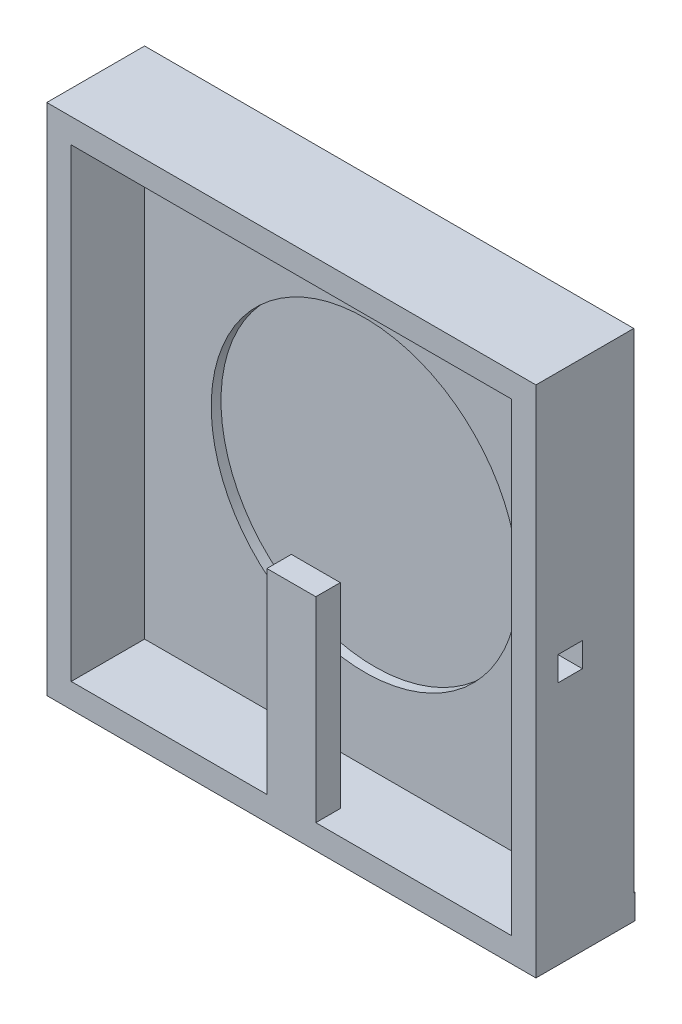
SolidWorks part; units mm, degrees
ref_plane "Front Plane" through (0, 0, 0) normal (0, 0, 1) x (1, 0, 0)
ref_plane "Top Plane" through (0, 0, 0) normal (0, 1, 0) x (1, 0, 0)
ref_plane "Right Plane" through (0, 0, 0) normal (1, 0, 0) x (0, 0, -1)
sketch "Sketch1" plane through (0, 0, 0) normal (0, 1, 0) x (1, 0, 0)
  line L1 (-750, 500) -> (750, 500)
  line L2 (-750, 500) -> (-750, -500)
  line L3 (-750, -500) -> (750, -500)
  line L4 (750, 500) -> (750, -500)
  line L5 (-750, 500) -> (750, -500) construction
  line L6 (-750, -500) -> (750, 500) construction
  point P0 (0, 0)
  dimension "D1" = 1500
  dimension "D2" = 1000
extrude "Boss-Extrude1" add sketch "Sketch1" along normal blind 50
sketch "Sketch2" plane through (0, 0, 0) normal (0, 0, 1) x (1, 0, 0)
  line L0 (-750, 50) -> (750, 50) construction
  line L1 (-500, 1050) -> (500, 1050)
  line L2 (-500, 1050) -> (-500, 50)
  line L3 (-500, 50) -> (500, 50)
  line L4 (500, 1050) -> (500, 50)
  point P6 (0, 50)
  dimension "D1" = 1000
  dimension "D2" = 1000
extrude "Boss-Extrude2" add sketch "Sketch2" against normal blind 200
sketch "Sketch3" plane through (0, 0, 0) normal (0, 0, 1) x (1, 0, 0)
  line L0 (-500, 50) -> (500, 50) construction
  line L5 (-450, 1000) -> (450, 1000)
  line L6 (-450, 1000) -> (-450, 50)
  line L7 (-450, 50) -> (450, 50)
  line L8 (450, 1000) -> (450, 50)
  line L9 (500, 50) -> (500, 1050) construction
  dimension "D1" = 900
  dimension "D2" = 50
  dimension "D3" = 950
extrude "Cut-Extrude1" cut sketch "Sketch3" against normal blind 150
sketch "Sketch4" plane through (0, 50, 0) normal (0, 1, 0) x (1, 0, 0)
  line L1 (-50, 50) -> (50, 50)
  line L2 (-50, 50) -> (-50, 0)
  line L3 (-50, 0) -> (50, 0)
  line L4 (50, 50) -> (50, 0)
  line L5 (450, 150) -> (450, 0) construction
  line L7 (-450, 150) -> (450, 150) construction
  dimension "D1" = 50
  dimension "D2" = 400
  dimension "D3" = 100
  dimension "D4" = 100
extrude "Boss-Extrude3" add sketch "Sketch4" along normal blind 400
sketch "Sketch5" plane through (500, 0, 0) normal (1, 0, 0) x (0, 0, -1)
  line L1 (45, 550) -> (95, 550)
  line L2 (45, 550) -> (45, 500)
  line L3 (45, 500) -> (95, 500)
  line L4 (95, 550) -> (95, 500)
  line L5 (45, 550) -> (95, 500) construction
  line L6 (45, 500) -> (95, 550) construction
  line L8 (200, 50) -> (0, 50) construction
  line L9 (200, 1050) -> (0, 1050) construction
  line L10 (0, 50) -> (0, 1050) construction
  point P0 (100, 550)
  point P5 (0, 0)
  point P7 (0, 0)
  point P8 (0, 0)
  point P10 (100, 50)
  point P15 (0, 0)
  dimension "D1" = 50
  dimension "D2" = 50
  dimension "D3" = 500
  dimension "D4" = 45
  dimension "D5" = 500
extrude "Cut-Extrude2" cut sketch "Sketch5" against normal blind 110
sketch "Sketch7" plane through (0, 50, 0) normal (0, 1, 0) x (1, 0, 0)
  line L0 (750, -500) -> (750, 500) construction
  line L1 (-750, -500) -> (750, -500)
  line L2 (-750, -500) -> (-750, 0)
  line L3 (-750, 0) -> (750, 0)
  line L4 (750, -500) -> (750, 0)
extrude "Cut-Extrude3" cut sketch "Sketch7" against normal through all
sketch "Sketch8" plane through (0, 50, 0) normal (0, 1, 0) x (1, 0, 0)
  line L0 (750, 0) -> (750, 500) construction
  line L1 (-750, 500) -> (750, 500)
  line L2 (-750, 500) -> (-750, 202.9738)
  line L3 (-750, 202.9738) -> (750, 202.9738)
  line L4 (750, 500) -> (750, 202.9738)
extrude "Cut-Extrude4" cut sketch "Sketch8" against normal through all
sketch "Sketch9" plane through (0, 50, 0) normal (0, 1, 0) x (1, 0, 0)
  line L1 (-750, 202.9738) -> (-500, 202.9738)
  line L2 (-750, 202.9738) -> (-750, 0)
  line L3 (-750, 0) -> (-500, 0)
  line L4 (-500, 202.9738) -> (-500, 0)
  line L5 (750, 202.9738) -> (500, 202.9738)
  line L6 (750, 202.9738) -> (750, 0)
  line L7 (750, 0) -> (500, 0)
  line L8 (500, 202.9738) -> (500, 0)
extrude "Cut-Extrude5" cut sketch "Sketch9" against normal through all
sketch "Sketch10" plane through (0, 0, -150) normal (0, 0, 1) x (1, 0, 0)
  line L0 (450, 50) -> (50, 50) construction
  circle A0 centre (0, 530) radius 313.8
  dimension "D2" = 627.6
  dimension "D1" = 480
extrude "Cut-Extrude6" cut sketch "Sketch10" against normal blind 20
